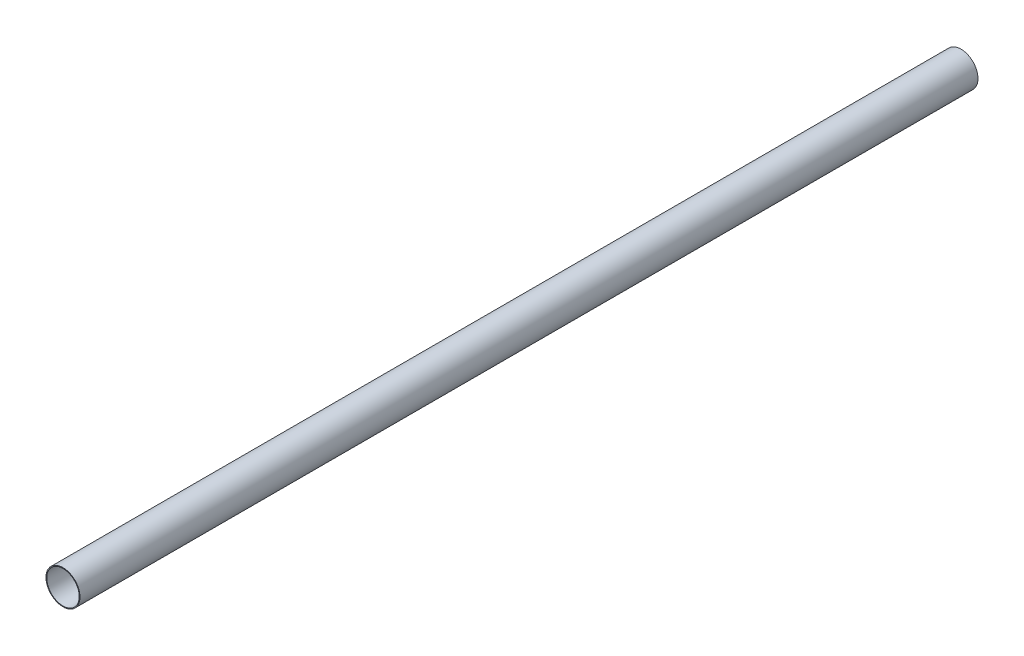
SolidWorks part; units mm, degrees
material "Thornel Mat VMA"
ref_plane "Front Plane" through (0, 0, 0) normal (0, 0, 1) x (1, 0, 0)
ref_plane "Top Plane" through (0, 0, 0) normal (0, 1, 0) x (1, 0, 0)
ref_plane "Right Plane" through (0, 0, 0) normal (1, 0, 0) x (0, 0, -1)
sketch "Sketch1" plane through (0, 0, 0) normal (0, 0, 1) x (1, 0, 0)
  circle A0 centre (0, 0) radius 1.5875
  circle A1 centre (0, 0) radius 1.5158
  dimension "D1" = 3.175
extrude "Boss-Extrude1" add sketch "Sketch1" along normal blind 83.82
